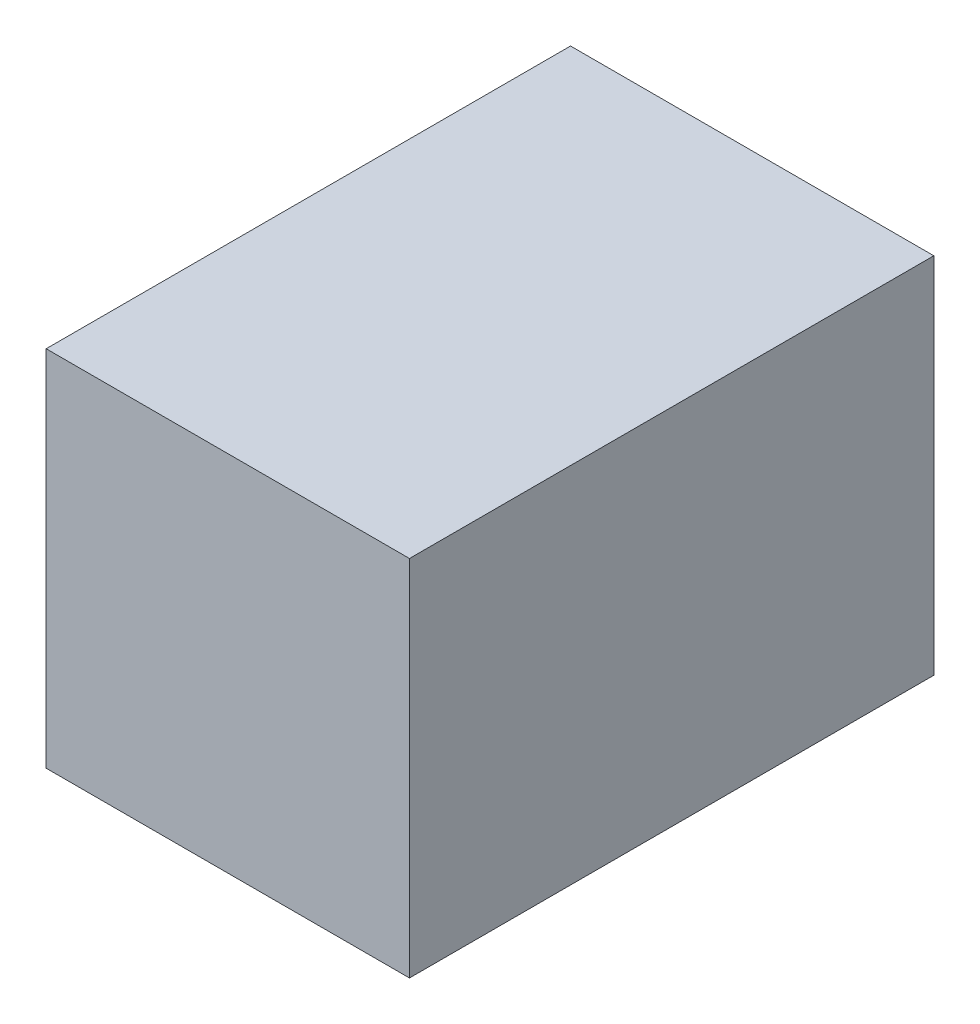
SolidWorks part; units mm, degrees
ref_plane "Front Plane" through (0, 0, 0) normal (0, 0, 1) x (1, 0, 0)
ref_plane "Top Plane" through (0, 0, 0) normal (0, 1, 0) x (1, 0, 0)
ref_plane "Right Plane" through (0, 0, 0) normal (1, 0, 0) x (0, 0, -1)
sketch "Sketch1" plane through (0, 0, 0) normal (0, 0, 1) x (1, 0, 0)
  line L0 (-3.3015, 3.3016) -> (3.3015, 3.3016)
  line L1 (3.3015, 3.3016) -> (3.3015, -3.3015)
  line L2 (3.3015, -3.3015) -> (-3.3015, -3.3015)
  line L3 (-3.3015, -3.3015) -> (-3.3015, 3.3016)
extrude "Component_Outline" add sketch "Sketch1" along normal blind 9.53 separate body
sketch3d "3DSketch1"
  line L0 (0, 0, 0) -> (1, 0, 0)
  line L1 (0, 0, 0) -> (0, 1, 0)
  line L2 (0, 0, 0) -> (0, 0, 1)
  point P0 (0, 0, 0)
